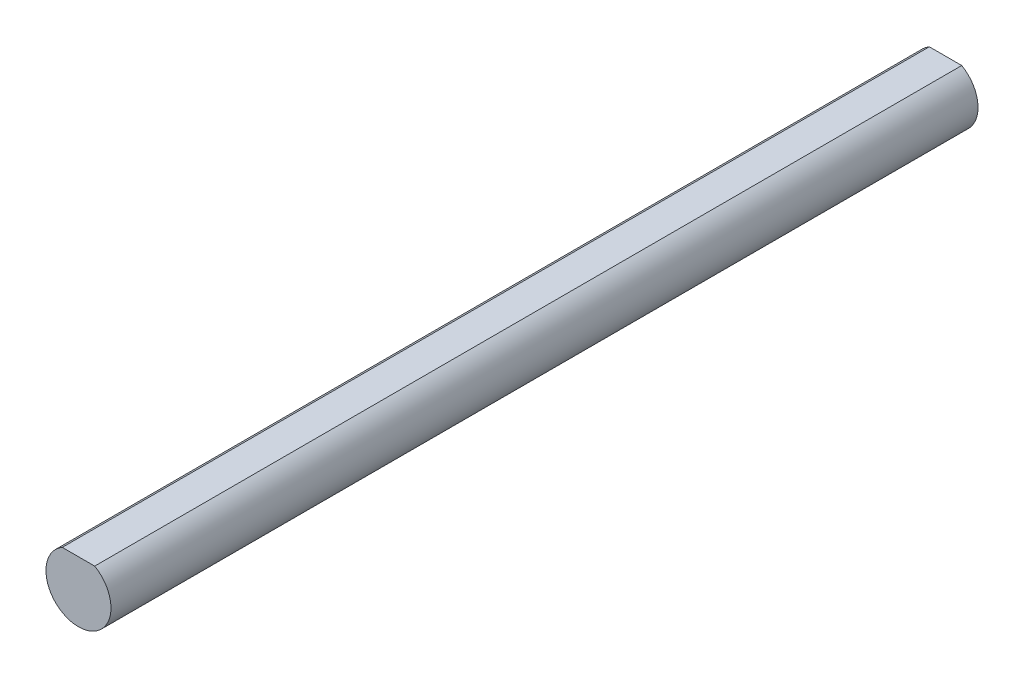
SolidWorks part; units mm, degrees
ref_plane "前视基准面" through (0, 0, 0) normal (0, 0, 1) x (1, 0, 0)
ref_plane "上视基准面" through (0, 0, 0) normal (0, 1, 0) x (1, 0, 0)
ref_plane "右视基准面" through (0, 0, 0) normal (1, 0, 0) x (0, 0, -1)
other "Configuration Table"
sketch "草图1" plane through (0, 0, 0) normal (1, 0, 0) x (0, 0, -1)
  line L0 (51, 0) -> (261, 0) construction
  line L1 (256, 0) -> (256, 7.5)
  line L2 (256, 7.5) -> (56, 7.5)
  line L3 (56, 7.5) -> (56, 0)
  line L4 (56, 0) -> (256, 0)
revolve "旋转1" add sketch "草图1" angle 360 about L0
sketch "草图2" plane through (0, 0, 0) normal (0, 0, 1) x (1, 0, 0)
  line L1 (-10, 6.5) -> (10, 6.5)
  line L2 (-10, 6.5) -> (-10, 12)
  line L3 (-10, 12) -> (10, 12)
  line L4 (10, 6.5) -> (10, 12)
extrude "切除-拉伸2" cut sketch "草图2" against normal through all
